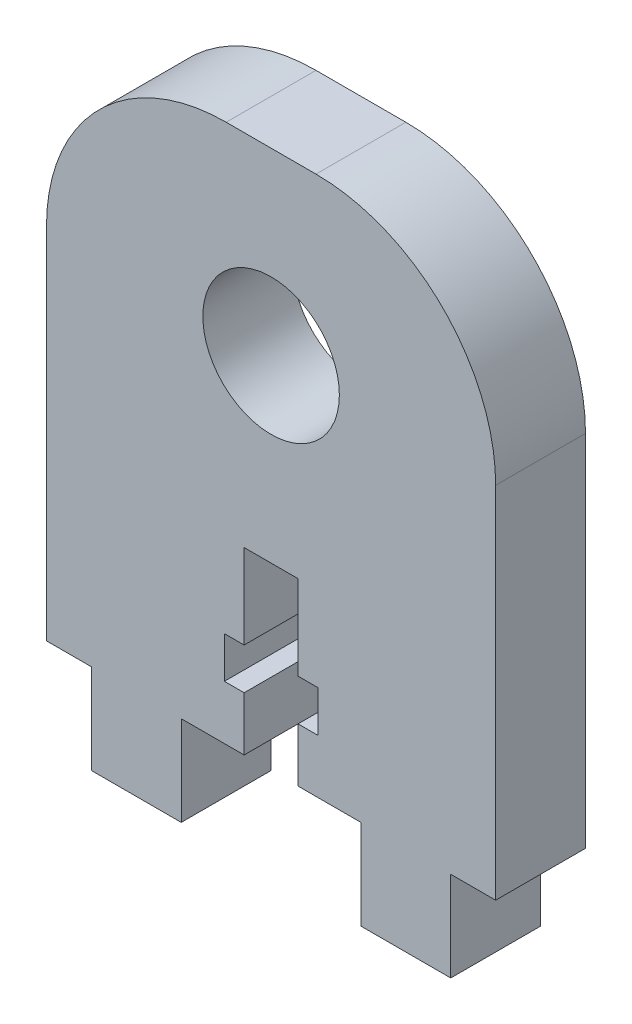
SolidWorks part; units mm, degrees
ref_plane "Front Plane" through (0, 0, 0) normal (0, 0, 1) x (1, 0, 0)
ref_plane "Top Plane" through (0, 0, 0) normal (0, 1, 0) x (1, 0, 0)
ref_plane "Right Plane" through (0, 0, 0) normal (1, 0, 0) x (0, 0, -1)
sketch "Sketch1" plane through (0, 0, 0) normal (0, 0, 1) x (1, 0, 0)
  line L1 (-12.5, -15) -> (12.5, -15)
  line L2 (-12.5, -15) -> (-12.5, 15)
  line L3 (-12.5, 15) -> (12.5, 15)
  line L4 (12.5, -15) -> (12.5, 15)
  line L5 (-12.5, -15) -> (12.5, 15) construction
  line L6 (-12.5, 15) -> (12.5, -15) construction
  circle A0 centre (0, 5) radius 3.8
  point P0 (0, 0)
  line B0 (-2.6, -12) -> (-2.6, -9.7)
  line B1 (1.5, -9.7) -> (1.5, -5)
  line B2 (-1.5, -5) -> (-1.5, -9.7)
  line B3 (-2.6, -9.7) -> (-1.5, -9.7)
  line B4 (0, -15) -> (0, -3.7792) construction
  line B5 (-1.5, -15) -> (-5, -15)
  line B6 (-5, -20) -> (-10, -20)
  line B7 (-10, -20) -> (-10, -15)
  line B8 (-5, -20) -> (-5, -15)
  line B9 (1.5, -15) -> (5, -15)
  line B10 (5, -15) -> (5, -20)
  line B11 (5, -20) -> (10, -20)
  line B12 (10, -20) -> (10, -15)
  line B13 (-1.5, -15) -> (1.5, -15) construction
  line B14 (1.5, -15) -> (1.5, -12)
  line B15 (1.5, -9.7) -> (2.6, -9.7)
  line B16 (2.6, -12) -> (1.5, -12)
  line B17 (1.5, -5) -> (-1.5, -5)
  line B18 (-1.5, -12) -> (-2.6, -12)
  line B19 (2.6, -9.7) -> (2.6, -12)
  line B20 (-1.5, -12) -> (-1.5, -15)
  line B21 (0, -5) -> (0, -15) construction
  dimension "D4" = 7.6
  dimension "D1" = 25
  dimension "D2" = 30
  dimension "D3" = 10
sketch_block_instance "Insert M3 plots ep 5mm-1"
sketch_block "Insert M3 plots ep 5mm" parameters "D1"=10, "D2"=5, "D3"=5
sketch_block_instance "Decoupe Insert M3-4"
sketch_block "Decoupe Insert M3" parameters "D1"=5.2, "D2"=3, "D3"=2.3, "D4"=3, "D5"=10
extrude "Boss-Extrude1" add sketch "Sketch1" along normal blind 5 contours B20 B18 B0 B3 B2 B17 B1 B15 B19 B16 B14 L1 L4 L3 L2 | B11 B12 L1 B10 | B6 B8 L1 B7
fillet "Fillet1" radius 10 2 edges at (-12.5, 15, 2.5) (12.5, 15, 2.5)
